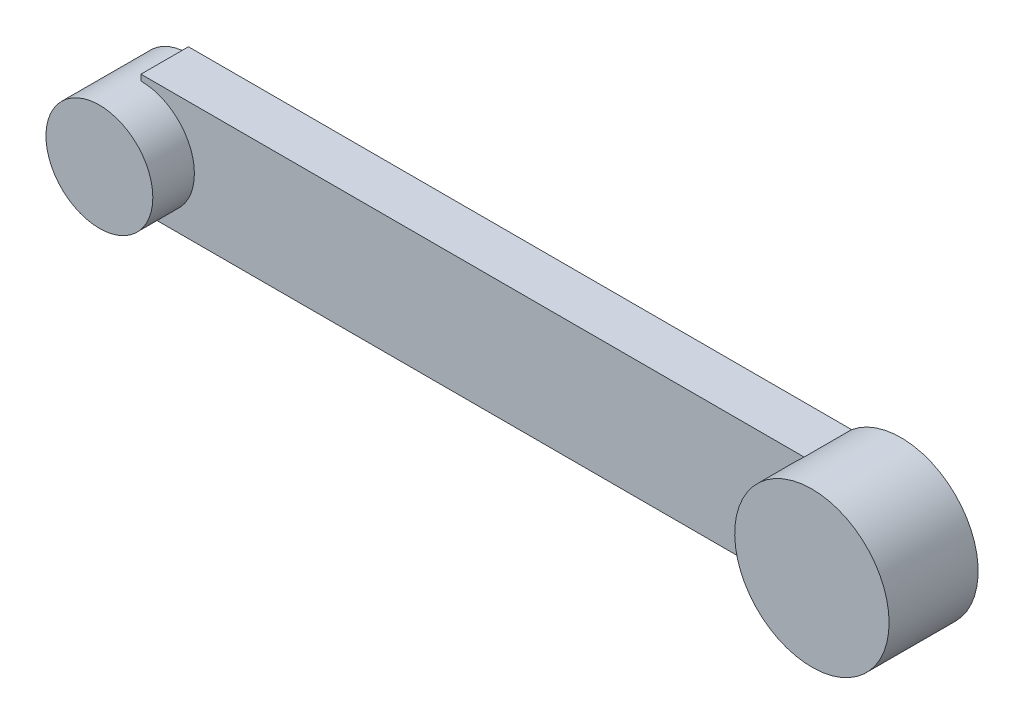
SolidWorks part; units mm, degrees
ref_plane "前视基准面" through (0, 0, 0) normal (0, 0, 1) x (1, 0, 0)
ref_plane "上视基准面" through (0, 0, 0) normal (0, 1, 0) x (1, 0, 0)
ref_plane "右视基准面" through (0, 0, 0) normal (1, 0, 0) x (0, 0, -1)
other "Configuration Table"
sketch "草图1" plane through (0, 0, 0) normal (0, 0, 1) x (1, 0, 0)
  line L1 (110000, 105000) -> (230000, 105000)
  line L2 (110000, 105000) -> (110000, 125000)
  line L3 (110000, 125000) -> (230000, 125000)
  line L4 (230000, 105000) -> (230000, 125000)
extrude "凸台-拉伸1" add sketch "草图1" along normal blind 8000
sketch "草图2" plane through (0, 0, 0) normal (0, 0, 1) x (1, 0, 0)
  line L0 (110000, 125000) -> (110000, 105000) construction
  circle A0 centre (110000, 115000) radius 9000
extrude "凸台-拉伸2" add sketch "草图2" along normal blind 15000
sketch "草图3" plane through (0, 0, 0) normal (0, 0, 1) x (1, 0, 0)
  line L0 (230000, 105000) -> (230000, 125000) construction
  circle A0 centre (230000, 115000) radius 13000
extrude "凸台-拉伸3" add sketch "草图3" along normal blind 15000
